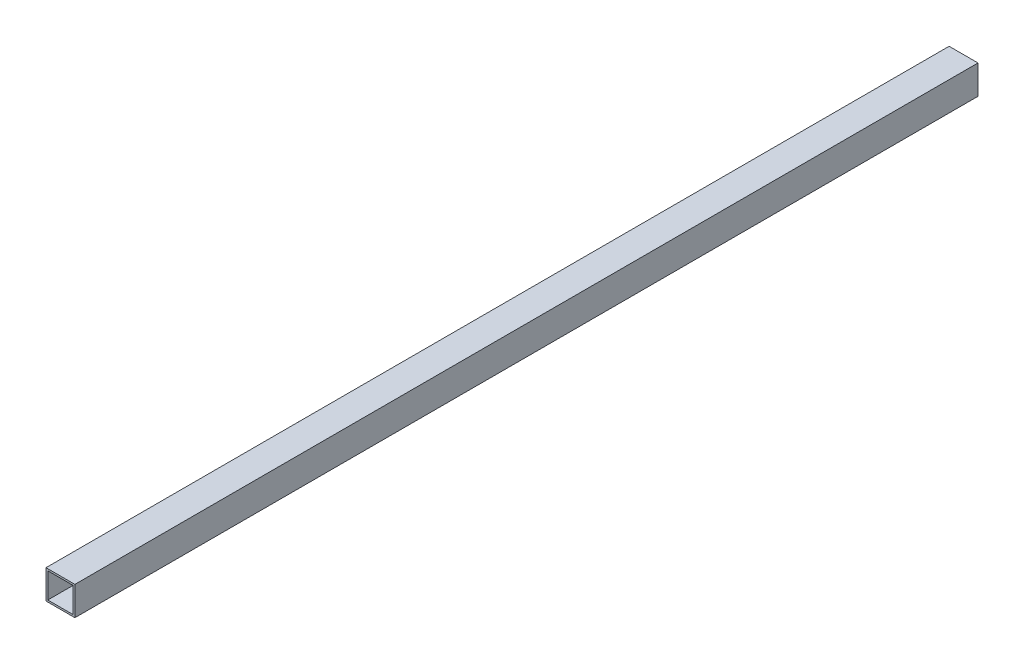
SolidWorks part; units mm, degrees
ref_plane "Front Plane" through (0, 0, 0) normal (0, 0, 1) x (1, 0, 0)
ref_plane "Top Plane" through (0, 0, 0) normal (0, 1, 0) x (1, 0, 0)
ref_plane "Right Plane" through (0, 0, 0) normal (1, 0, 0) x (0, 0, -1)
sketch "Sketch2" plane through (0, 0, 0) normal (0, 0, 1) x (1, 0, 0)
  line L1 (0, 0) -> (8, 0)
  line L2 (0, 0) -> (0, 8)
  line L3 (0, 8) -> (8, 8)
  line L4 (8, 0) -> (8, 8)
  line L5 (0.5, 7.5) -> (7.5, 7.5)
  line L6 (0.5, 7.5) -> (0.5, 0.5)
  line L7 (0.5, 0.5) -> (7.5, 0.5)
  line L8 (7.5, 7.5) -> (7.5, 0.5)
  point P9 (0, 4)
  point P10 (4, 8)
  dimension "D1" = 8
  dimension "D2" = 8
  dimension "D3" = 7
  dimension "D4" = 7
  dimension "D5" = 3.5
  dimension "D6" = 3.5
extrude "Boss-Extrude1" add sketch "Sketch2" along normal blind 250
